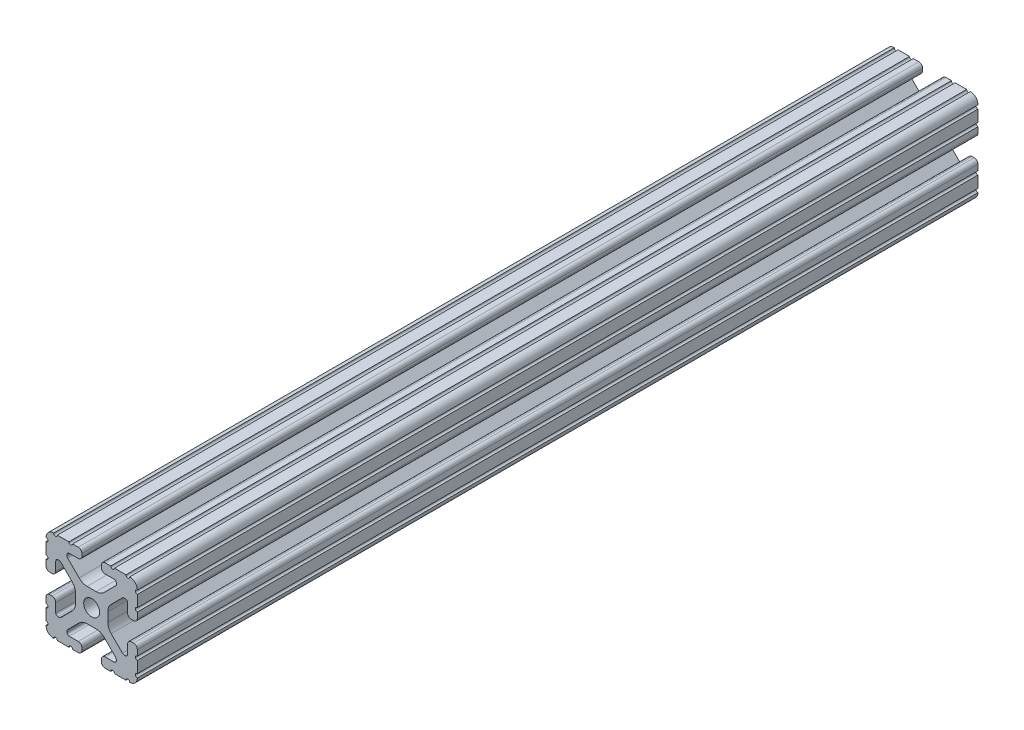
SolidWorks part; units mm, degrees
material "6061 Alloy"
ref_plane "Front Plane" through (0, 0, 0) normal (0, 0, 1) x (1, 0, 0)
ref_plane "Top Plane" through (0, 0, 0) normal (0, 1, 0) x (1, 0, 0)
ref_plane "Right Plane" through (0, 0, 0) normal (1, 0, 0) x (0, 0, -1)
sketch "Sketch1" plane through (0, 0, 0) normal (0, 0, 1) x (1, 0, 0)
  line L0 (0, 25.6181) -> (0, -24.623) construction
  line L1 (-20.8943, 0) -> (20.4607, 0) construction
  line L2 (-10.0229, 12.9148) -> (-5.2522, 8.144)
  line L3 (-10.287, 14.0843) -> (-10.287, 13.5524)
  line L4 (-5.6176, 14.986) -> (-9.3853, 14.986)
  line L5 (-4.064, 17.4964) -> (-4.064, 16.5396)
  line L6 (-7.9742, 19.05) -> (-5.6176, 19.05)
  line L7 (-14.3277, 19.05) -> (-9.4982, 19.05)
  line L8 (-19.05, 9.4961) -> (-19.05, 14.3277)
  line L9 (-19.05, 5.6176) -> (-19.05, 7.9763)
  line L10 (-16.5396, 4.064) -> (-17.4964, 4.064)
  line L11 (-14.986, 9.3853) -> (-14.986, 5.6176)
  line L12 (-13.516, 10.287) -> (-14.0843, 10.287)
  line L13 (-8.1476, 5.2921) -> (-12.8784, 10.0229)
  line L14 (-6.7564, -1.9335) -> (-6.7564, 1.9335)
  line L15 (-12.8784, -10.0229) -> (-8.1476, -5.2921)
  line L16 (-14.0843, -10.287) -> (-13.516, -10.287)
  line L17 (-14.986, -5.6176) -> (-14.986, -9.3853)
  line L18 (-17.4964, -4.064) -> (-16.5396, -4.064)
  line L19 (-19.05, -7.9763) -> (-19.05, -5.6176)
  line L20 (-19.05, -14.3277) -> (-19.05, -9.4961)
  line L21 (-9.4961, -19.05) -> (-14.3277, -19.05)
  line L22 (-5.6176, -19.05) -> (-7.9763, -19.05)
  line L23 (-4.064, -17.4964) -> (-4.064, -16.5396)
  line L24 (10.0229, -12.9148) -> (5.2522, -8.144)
  line L25 (10.287, -14.0843) -> (10.287, -13.5524)
  line L26 (5.6176, -14.986) -> (9.3853, -14.986)
  line L28 (-1.9022, 6.7564) -> (1.9022, 6.7564)
  line L29 (-1.9022, -6.7564) -> (1.9022, -6.7564)
  line L31 (-5.6176, -14.986) -> (-9.3853, -14.986)
  line L32 (-10.287, -14.0843) -> (-10.287, -13.5524)
  line L33 (-10.0229, -12.9148) -> (-5.2522, -8.144)
  line L66 (4.064, -16.5396) -> (4.064, -17.4964)
  line L67 (5.6176, -19.05) -> (7.9763, -19.05)
  line L68 (9.4961, -19.05) -> (14.3277, -19.05)
  line L69 (19.05, -14.3277) -> (19.05, -9.4961)
  line L70 (19.05, -7.9763) -> (19.05, -5.6176)
  line L71 (17.4964, -4.064) -> (16.5396, -4.064)
  line L72 (14.986, -5.6176) -> (14.986, -9.3853)
  line L73 (14.0843, -10.287) -> (13.516, -10.287)
  line L74 (12.8784, -10.0229) -> (8.1476, -5.2921)
  line L75 (6.7564, -1.9335) -> (6.7564, 1.9335)
  line L76 (8.1476, 5.2921) -> (12.8784, 10.0229)
  line L77 (13.516, 10.287) -> (14.0843, 10.287)
  line L78 (14.986, 9.3853) -> (14.986, 5.6176)
  line L79 (16.5396, 4.064) -> (17.4964, 4.064)
  line L80 (19.05, 5.6176) -> (19.05, 7.9763)
  line L81 (19.05, 9.4961) -> (19.05, 14.3277)
  line L82 (14.3277, 19.05) -> (9.4982, 19.05)
  line L83 (7.9742, 19.05) -> (5.6176, 19.05)
  line L84 (4.064, 17.4964) -> (4.064, 16.5396)
  line L85 (5.6176, 14.986) -> (9.3853, 14.986)
  line L86 (10.287, 14.0843) -> (10.287, 13.5524)
  line L87 (10.0229, 12.9148) -> (5.2522, 8.144)
  arc A0 (-10.0229, 12.9148) -> (-10.287, 13.5524) centre (-9.3853, 13.5524) cw
  circle A1 centre (0, 0) radius 3.3274
  arc A2 (-10.287, 14.0843) -> (-9.3853, 14.986) centre (-9.3853, 14.0843) cw
  arc A3 (-4.064, 16.5396) -> (-5.6176, 14.986) centre (-5.6176, 16.5396) cw
  arc A4 (-5.6176, 19.05) -> (-4.064, 17.4964) centre (-5.6176, 17.4964) cw
  arc A5 (-7.9742, 19.05) -> (-9.4982, 19.05) centre (-8.7362, 19.05) cw
  arc A6 (-14.3277, 19.05) -> (-15.8475, 19.05) centre (-15.0876, 18.9933) cw
  arc A7 (-19.05, 15.8475) -> (-15.8475, 19.05) centre (-15.8751, 15.8751) cw
  arc A8 (-19.05, 15.8475) -> (-19.05, 14.3277) centre (-18.9933, 15.0876) cw
  arc A9 (-19.05, 9.4961) -> (-19.05, 7.9763) centre (-18.9933, 8.7362) cw
  arc A10 (-17.4964, 4.064) -> (-19.05, 5.6176) centre (-17.4964, 5.6176) cw
  arc A11 (-14.986, 5.6176) -> (-16.5396, 4.064) centre (-16.5396, 5.6176) cw
  arc A12 (-14.986, 9.3853) -> (-14.0843, 10.287) centre (-14.0843, 9.3853) cw
  arc A13 (-13.516, 10.287) -> (-12.8784, 10.0229) centre (-13.516, 9.3853) cw
  arc A14 (-8.1476, 5.2921) -> (-6.7564, 1.9335) centre (-11.5062, 1.9335) cw
  arc A15 (-6.7564, -1.9335) -> (-8.1476, -5.2921) centre (-11.5062, -1.9335) cw
  arc A16 (-12.8784, -10.0229) -> (-13.516, -10.287) centre (-13.516, -9.3853) cw
  arc A17 (-14.0843, -10.287) -> (-14.986, -9.3853) centre (-14.0843, -9.3853) cw
  arc A18 (-16.5396, -4.064) -> (-14.986, -5.6176) centre (-16.5396, -5.6176) cw
  arc A19 (-19.05, -5.6176) -> (-17.4964, -4.064) centre (-17.4964, -5.6176) cw
  arc A20 (-19.05, -7.9763) -> (-19.05, -9.4961) centre (-18.9933, -8.7362) cw
  arc A21 (-19.05, -14.3277) -> (-19.05, -15.8475) centre (-18.9933, -15.0876) cw
  arc A22 (-15.8475, -19.05) -> (-19.05, -15.8475) centre (-15.8751, -15.8751) cw
  arc A23 (-15.8475, -19.05) -> (-14.3277, -19.05) centre (-15.0876, -18.9933) cw
  arc A24 (-9.4961, -19.05) -> (-7.9763, -19.05) centre (-8.7362, -18.9933) cw
  arc A25 (-4.064, -17.4964) -> (-5.6176, -19.05) centre (-5.6176, -17.4964) cw
  arc A26 (-5.2522, -8.144) -> (-1.9022, -6.7564) centre (-1.9022, -11.494) cw
  arc A27 (1.9022, -6.7564) -> (5.2522, -8.144) centre (1.9022, -11.494) cw
  arc A28 (10.0229, -12.9148) -> (10.287, -13.5524) centre (9.3853, -13.5524) cw
  arc A29 (10.287, -14.0843) -> (9.3853, -14.986) centre (9.3853, -14.0843) cw
  arc A30 (4.064, -16.5396) -> (5.6176, -14.986) centre (5.6176, -16.5396) cw
  arc A31 (-4.064, -16.5396) -> (-5.6176, -14.986) centre (-5.6176, -16.5396) ccw
  arc A32 (-10.287, -14.0843) -> (-9.3853, -14.986) centre (-9.3853, -14.0843) ccw
  arc A33 (-10.0229, -12.9148) -> (-10.287, -13.5524) centre (-9.3853, -13.5524) ccw
  arc A79 (4.064, -17.4964) -> (5.6176, -19.05) centre (5.6176, -17.4964) ccw
  arc A80 (9.4961, -19.05) -> (7.9763, -19.05) centre (8.7362, -18.9933) ccw
  arc A81 (15.8475, -19.05) -> (14.3277, -19.05) centre (15.0876, -18.9933) ccw
  arc A82 (15.8475, -19.05) -> (19.05, -15.8475) centre (15.8751, -15.8751) ccw
  arc A83 (19.05, -14.3277) -> (19.05, -15.8475) centre (18.9933, -15.0876) ccw
  arc A84 (19.05, -7.9763) -> (19.05, -9.4961) centre (18.9933, -8.7362) ccw
  arc A85 (19.05, -5.6176) -> (17.4964, -4.064) centre (17.4964, -5.6176) ccw
  arc A86 (16.5396, -4.064) -> (14.986, -5.6176) centre (16.5396, -5.6176) ccw
  arc A87 (14.0843, -10.287) -> (14.986, -9.3853) centre (14.0843, -9.3853) ccw
  arc A88 (12.8784, -10.0229) -> (13.516, -10.287) centre (13.516, -9.3853) ccw
  arc A89 (6.7564, -1.9335) -> (8.1476, -5.2921) centre (11.5062, -1.9335) ccw
  arc A90 (8.1476, 5.2921) -> (6.7564, 1.9335) centre (11.5062, 1.9335) ccw
  arc A91 (13.516, 10.287) -> (12.8784, 10.0229) centre (13.516, 9.3853) ccw
  arc A92 (14.986, 9.3853) -> (14.0843, 10.287) centre (14.0843, 9.3853) ccw
  arc A93 (14.986, 5.6176) -> (16.5396, 4.064) centre (16.5396, 5.6176) ccw
  arc A94 (17.4964, 4.064) -> (19.05, 5.6176) centre (17.4964, 5.6176) ccw
  arc A95 (19.05, 9.4961) -> (19.05, 7.9763) centre (18.9933, 8.7362) ccw
  arc A96 (19.05, 15.8475) -> (19.05, 14.3277) centre (18.9933, 15.0876) ccw
  arc A97 (19.05, 15.8475) -> (15.8475, 19.05) centre (15.8751, 15.8751) ccw
  arc A98 (14.3277, 19.05) -> (15.8475, 19.05) centre (15.0876, 18.9933) ccw
  arc A99 (7.9742, 19.05) -> (9.4982, 19.05) centre (8.7362, 19.05) ccw
  arc A100 (5.6176, 19.05) -> (4.064, 17.4964) centre (5.6176, 17.4964) ccw
  arc A101 (4.064, 16.5396) -> (5.6176, 14.986) centre (5.6176, 16.5396) ccw
  arc A102 (10.287, 14.0843) -> (9.3853, 14.986) centre (9.3853, 14.0843) ccw
  arc A103 (10.0229, 12.9148) -> (10.287, 13.5524) centre (9.3853, 13.5524) ccw
  arc A104 (1.9022, 6.7564) -> (5.2522, 8.144) centre (1.9022, 11.494) ccw
  arc A105 (-5.2522, 8.144) -> (-1.9022, 6.7564) centre (-1.9022, 11.494) ccw
  dimension "D1" = 6.6548
  dimension "D2" = 19.05
  dimension "D3" = 38.1
  dimension "D4" = 20.574
  dimension "D5" = 13.5128
  dimension "D6" = 4.064
  dimension "D7" = 8.128
  dimension "D8" = 4.064
  dimension "D9" = 12.2936
extrude "Extrude1" add sketch "Sketch1" against normal blind 350.8
